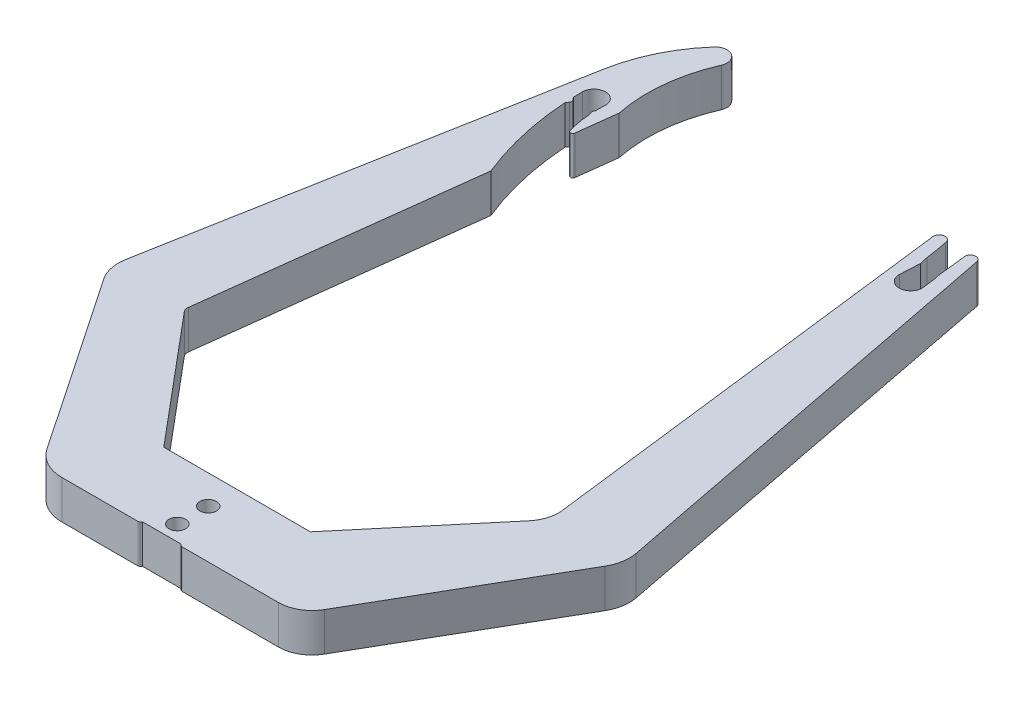
SolidWorks part; units mm, degrees
ref_plane "前视基准面" through (0, 0, 0) normal (0, 0, 1) x (1, 0, 0)
ref_plane "上视基准面" through (0, 0, 0) normal (0, 1, 0) x (1, 0, 0)
ref_plane "右视基准面" through (0, 0, 0) normal (1, 0, 0) x (0, 0, -1)
sketch "草图1" plane through (0, 0, 0) normal (0, 1, 0) x (1, 0, 0)
  line L0 (0, 0) -> (0, -20) construction
  line L1 (-19, 0) -> (19, 0)
  line L2 (-35.7227, -20) -> (35.7227, -20) construction
  line L3 (19, 0) -> (44.8546, 30.8123)
  line L4 (46.8223, 37.4552) -> (33.3895, 146.8562)
  line L5 (38.2306, -15.6563) -> (64.8605, 30.468)
  line L6 (66.0165, 37.3761) -> (44.728, 146.8959)
  line L7 (-5, -19.5) -> (5, -19.5)
  line L8 (5, -19.5) -> (5.3536, -19.8536)
  line L9 (5.7071, -20) -> (30.7071, -20)
  line L10 (-5, -19.5) -> (-5.3536, -19.8536)
  line L11 (-5.7071, -20) -> (-25.3998, -20)
  line L12 (-35.7227, -20) -> (-64.8605, 30.468) construction
  line L13 (-19, 0) -> (-46.7237, 33.0398)
  line L14 (-47.2827, 33.706) -> (-33.3895, 146.8562) construction
  line L15 (-66.0165, 37.3761) -> (-46.8296, 141.8909)
  line L18 (-34.9739, 133.9531) -> (-47.1767, 34.5691)
  line L44 (-64.8605, 30.468) -> (-33.6816, -15.6046)
  line L45 (43.5031, 134.5037) -> (43.077, 137.8137)
  line L46 (42.1293, 145.1753) -> (42.8054, 138.9383)
  line L47 (42.8076, 138.9256) -> (43.077, 137.8137)
  line L48 (37.3208, 141.4732) -> (37.8151, 139.2584)
  line L49 (42.1293, 145.1753) -> (41.9652, 146.45)
  line L50 (37.8174, 139.2316) -> (37.5579, 134.1048)
  arc A0 (64.8605, 30.468) -> (66.0165, 37.3761) centre (56.2002, 35.468) ccw
  arc A1 (-64.8605, 30.468) -> (-66.0165, 37.3761) centre (-56.2002, 35.468) cw
  arc A2 (33.3895, 146.8562) -> (36.3769, 147.1048) centre (34.8784, 147.039) cw
  arc A4 (37.5579, 134.1048) -> (43.5031, 134.5037) centre (40.5541, 133.9531) ccw
  arc A5 (44.728, 146.8959) -> (41.9652, 146.45) centre (43.3537, 146.6287) ccw
  arc A7 (-46.8296, 141.8909) -> (-37.4802, 161.1337) centre (-7.4871, 134.6684) cw
  arc A8 (-37.4802, 161.1337) -> (-32.4793, 157.9531) centre (-35.2307, 159.1488) cw
  arc A9 (-32.4793, 157.9531) -> (-34.9739, 133.9531) centre (4.2063, 142.0103) ccw
  arc A10 (-46.7237, 33.0398) -> (-47.1767, 34.5691) centre (-45.1916, 34.3254) cw
  arc A19 (38.2306, -15.6563) -> (30.7071, -20) centre (30.7071, -11.3127) cw
  arc A20 (44.8546, 30.8123) -> (46.8223, 37.4552) centre (38.1997, 36.3964) ccw
  arc A21 (5.3536, -19.8536) -> (5.7071, -20) centre (5.7071, -19.5) ccw
  arc A22 (-5.3536, -19.8536) -> (-5.7071, -20) centre (-5.7071, -19.5) cw
  arc A34 (-25.3998, -20) -> (-33.6816, -15.6046) centre (-25.3998, -10) cw
  arc A37 (42.8054, 138.9383) -> (42.8076, 138.9256) centre (42.9048, 138.9491) ccw
  arc A38 (37.8151, 139.2584) -> (37.8174, 139.2316) centre (37.7175, 139.2366) cw
  arc A39 (36.3769, 147.1048) -> (37.3208, 141.4732) centre (-54.0014, 129.0619) cw
  point P7 (0, 0)
  point P9 (0, -20)
  point P18 (66.7299, 33.706)
  point P24 (0, -19.5)
  point P34 (0, 0)
  point P43 (-30.7071, -20)
  point P50 (46.8296, 141.8909)
  point P53 (42.8061, 138.9319)
  point P60 (0, 0)
  point P61 (0, 0)
  point P62 (40.5541, 133.9531)
  point P63 (0, 0)
  point P76 (-42.7886, -7.7616)
  point P85 (47.2827, 33.706)
  point P88 (5.5, -20)
  point P91 (-5.5, -20)
  dimension "D14" = 10
  dimension "D17" = 1.5
  dimension "D18" = 3
  dimension "1.4" = 1.4
  dimension "D23" = 40
  dimension "D24" = 3
  dimension "D26" = 40
  dimension "D30" = 2
  dimension "D39" = 0.5
  dimension "D28" = 10
  dimension "D15" = 4.8
  dimension "D16" = 0.1
  dimension "D1" = 20
  dimension "D2" = 38
  dimension "D4" = 130
  dimension "D5" = 44
  dimension "D6" = 133
  dimension "D7" = 114
  dimension "D8" = 120
  dimension "D9" = 139
  dimension "D10" = 110
  dimension "D11" = 5
  dimension "D12" = 1
  dimension "D13" = 135
  dimension "D19" = 13
  dimension "D25" = 13
  dimension "D27" = 24
  dimension "D29" = 25
  dimension "D31" = 25
extrude "凸台-拉伸1" add sketch "草图1" along normal blind 10
sketch "草图2" plane through (0, 10, 0) normal (0, 1, 0) x (1, 0, 0)
  line L0 (-47.1767, 34.5691) -> (-34.9739, 133.9531) construction
  line L2 (-36.5496, 121.12) -> (-38.6077, 104.3574)
  line L3 (-5, -19.5) -> (5, -19.5) construction
  line L4 (-38.7444, 130.4462) -> (-38.4867, 129.7939)
  line L9 (40.5541, 133.9531) -> (-57.9515, 133.9531) construction
  line L11 (-38.5563, 131.3155) -> (-38.5461, 131.3251)
  line L12 (-44.4474, 131.5436) -> (-43.9248, 131.0031)
  line L13 (-43.8451, 129.9874) -> (-44.3325, 129.293)
  arc A0 (-38.6077, 104.3574) -> (-44.3325, 129.293) centre (35.4981, 134.4958) cw
  circle A3 centre (0, -15.5) radius 2.15
  circle A4 centre (0, -7.5) radius 2.15
  arc A7 (-38.5057, 133.7686) -> (-38.5563, 131.3155) centre (-8.5625, 131.9238) ccw
  arc A13 (-38.5057, 133.7686) -> (-44.4999, 133.932) centre (-41.5, 133.9531) ccw
  arc A14 (-44.4474, 131.5436) -> (-44.4999, 133.932) centre (35.4981, 134.4958) cw
  arc A15 (-38.4867, 129.7939) -> (-36.5496, 121.12) centre (-8.5625, 131.9238) ccw
  arc A16 (-38.5461, 131.3251) -> (-38.7444, 130.4462) centre (-38.0003, 130.7401) ccw
  arc A17 (-43.9248, 131.0031) -> (-43.8451, 129.9874) centre (-44.4999, 130.447) cw
  point P6 (-36.3133, 123.0442)
  point P22 (-38.4181, 105.7519)
  point P23 (-36.6667, 120.1663)
  point P26 (0, 0)
  point P30 (-38.9446, 130.9532)
  point P32 (-38.4181, 119.1092)
  point P34 (-43.4656, 130.5282)
  point P35 (-38.4181, 104.7063)
  point P37 (-36.7965, 119.1092)
  point P38 (0, 0)
  point P39 (-38.8193, 131.0857)
  point P40 (-43.8766, 130.571)
  point P41 (-44.2976, 129.3236)
  point P42 (-43.7305, 130.5416)
  point P43 (-44.3347, 129.8106)
  point P44 (0, 0)
  point P45 (-41.5, 133.9255)
  point P46 (-41.5, 134.007)
  point P47 (-36.6225, 120.5259)
  point P48 (-36.5496, 121.12)
  point P49 (-38.5408, 104.9025)
  point P50 (0, 0)
  point P51 (-43.6381, 130.6133)
  point P52 (0, 0)
  point P53 (-38.7791, 130.9709)
  point P54 (-38.6077, 104.3574)
  point P55 (0, 0)
  point P56 (-44.4474, 130.5282)
  dimension "D5" = 3
  dimension "D6" = 30
  dimension "D7" = 80
  dimension "D9" = 4.3
  dimension "D12" = 0.8
  dimension "D4" = 41.5
  dimension "D8" = 8
  dimension "D10" = 4
extrude "切除-拉伸1" cut sketch "草图2" against normal up to next
fillet "圆角1" radius 0.6 2 edges at (-34.9739, 5, -133.9531) (-36.5496, 5, -121.12)
